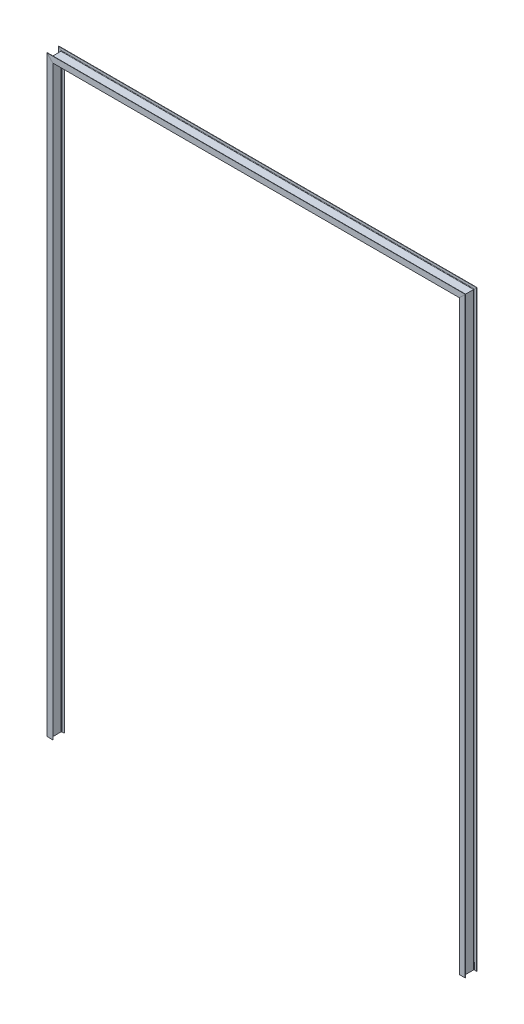
SolidWorks part; units mm, degrees
material "ASTM A36 Steel"
ref_plane "Front Plane" through (0, 0, 0) normal (0, 0, 1) x (1, 0, 0)
ref_plane "Top Plane" through (0, 0, 0) normal (0, 1, 0) x (1, 0, 0)
ref_plane "Right Plane" through (0, 0, 0) normal (1, 0, 0) x (0, 0, -1)
sketch "Sketch1" plane through (0, 0, 0) normal (0, 0, 1) x (1, 0, 0)
  line L0 (0, 0) -> (0, 10000)
  line L1 (0, 10000) -> (7000, 10000)
  line L2 (7000, 10000) -> (7000, 0)
  dimension "D1" = 10000
  dimension "D2" = 7000
other "W section W8X10(1)"
ref_plane "Plane1" through (0, 0, 0) normal (0, 1, 0) x (-1, 0, 0)
sketch "Sketch11" plane through (0, 0, 0) normal (0, 1, 0) x (-1, 0, 0)
  line L0 (-50.038, -100.203) -> (-50.038, -94.996)
  line L1 (-50.038, -94.996) -> (-9.779, -94.996)
  line L2 (-2.159, -87.376) -> (-2.159, 87.376)
  line L3 (-9.779, 94.996) -> (-50.038, 94.996)
  line L4 (-50.038, 94.996) -> (-50.038, 100.203)
  line L5 (-50.038, 100.203) -> (50.038, 100.203)
  line L6 (50.038, 100.203) -> (50.038, 94.996)
  line L7 (50.038, 94.996) -> (9.779, 94.996)
  line L8 (2.159, 87.376) -> (2.159, -87.376)
  line L9 (9.779, -94.996) -> (50.038, -94.996)
  line L10 (50.038, -94.996) -> (50.038, -100.203)
  line L11 (50.038, -100.203) -> (-50.038, -100.203)
  line L12 (0, 0) -> (0, 100.203) construction
  line L13 (-2.159, 0) -> (2.159, 0) construction
  arc A0 (-9.779, -94.996) -> (-2.159, -87.376) centre (-9.779, -87.376) ccw
  arc A1 (-2.159, 87.376) -> (-9.779, 94.996) centre (-9.779, 87.376) ccw
  arc A2 (9.779, 94.996) -> (2.159, 87.376) centre (9.779, 87.376) ccw
  arc A3 (2.159, -87.376) -> (9.779, -94.996) centre (9.779, -87.376) ccw
  point P23 (-50.038, 0)
  point P26 (0, -100.203)
  point P27 (50.038, 0)
  point P28 (0, 0)
  dimension "Ri" = 7.62
  dimension "D1" = 2.159
  dimension "D2" = 5.207
  dimension "Tw" = 4.318
  dimension "Bf" = 100.076
  dimension "Depth" = 200.406
  dimension "Tf" = 5.207
